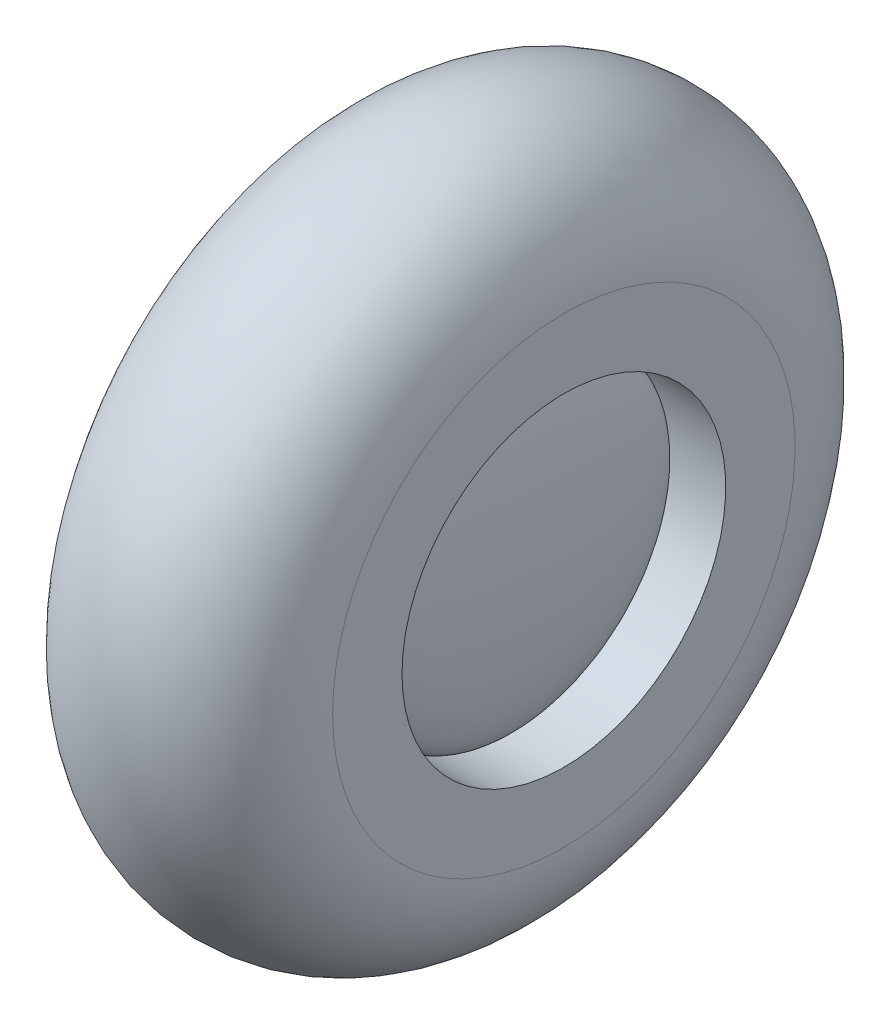
SolidWorks part; units mm, degrees
material "Choose your Material"
ref_plane "Front Plane" through (0, 0, 0) normal (0, 0, 1) x (1, 0, 0)
ref_plane "Top Plane" through (0, 0, 0) normal (0, 1, 0) x (1, 0, 0)
ref_plane "Right Plane" through (0, 0, 0) normal (1, 0, 0) x (0, 0, -1)
sketch "Sketch3" plane through (0, 0, 0) normal (0, 0, 1) x (1, 0, 0)
  line L0 (0, 0) -> (54643.4738, 0) construction
  line L1 (-82.8675, 0) -> (82.8675, 0)
  line L3 (-110.49, 150.6855) -> (-110.49, 215.265)
  line L4 (-110.49, 150.6855) -> (-55.245, 150.6855)
  line L5 (-82.8675, 150.6855) -> (-82.8675, 0) construction
  line L6 (-82.8675, -68.6429) -> (-82.8675, 68.7741) construction
  line L7 (-73.037, 150.6855) -> (-37.1122, 150.6855) construction
  line L8 (0, 0) -> (0, 215.265) construction
  line L9 (110.49, 150.6855) -> (110.49, 215.265)
  line L10 (82.8675, 150.6855) -> (82.8675, 0) construction
  line L11 (110.49, 150.6855) -> (55.245, 150.6855)
  arc A0 (-110.49, 215.265) -> (110.49, 215.265) centre (0, 215.265) cw
  spline S0 degree 3 poles (-55.245, 150.6855) (-77.698, 150.6855) (-82.8675, 43.6827) (-82.8675, 0) knots 0 0 0 0 1 1 1 1
  spline S1 degree 3 poles (55.245, 150.6855) (77.698, 150.6855) (82.8675, 43.6827) (82.8675, 0) knots 0 0 0 0 1 1 1 1
  point P6 (0, 0)
  dimension "D2" = 110.49
  dimension "D1" = 215.265
  dimension "D3" = 150.6855
  dimension "D4" = 55.245
revolve "Revolve1" add sketch "Sketch3" angle 360 about L0
equation "\"wheelwidth\"=8.7"
equation "\"D2@Sketch3\"=\"wheelwidth\"/2"
equation "\"diameter\"=25.65"
equation "\"D1@Sketch3\"=\"diameter\"/2-\"wheelwidth\"/2"
equation "\"D3@Sketch3\"=(\"diameter\"/2-\"wheelwidth\"/2)*0.7"
equation "\"D4@Sketch3\"=\"wheelwidth\"/4"
